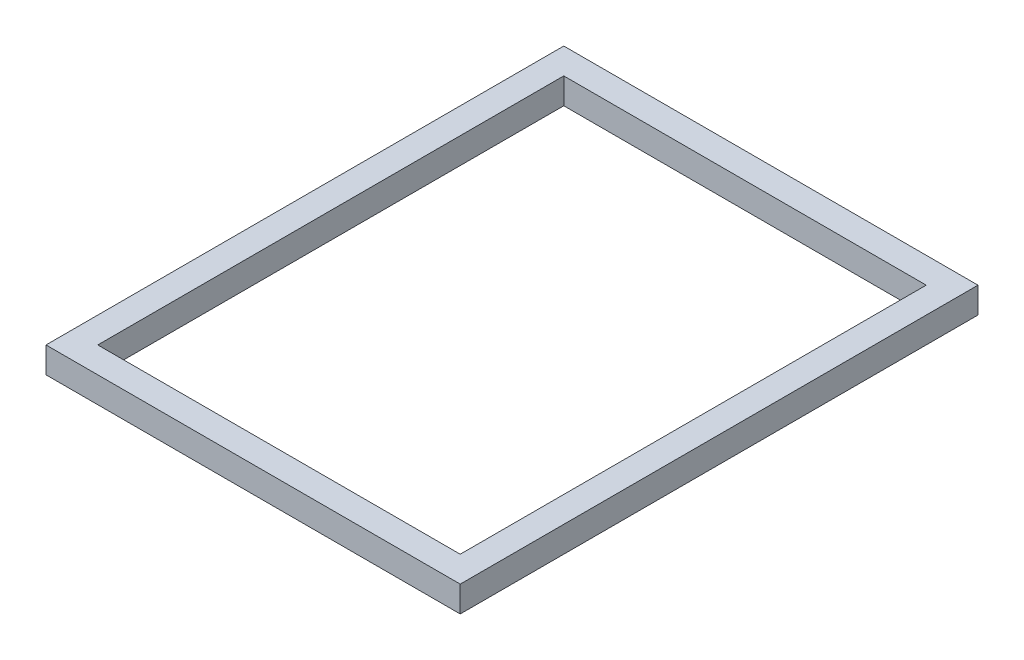
SolidWorks part; units mm, degrees
material "Silicon Rubber"
ref_plane "Front Plane" through (0, 0, 0) normal (0, 0, 1) x (1, 0, 0)
ref_plane "Top Plane" through (0, 0, 0) normal (0, 1, 0) x (1, 0, 0)
ref_plane "Right Plane" through (0, 0, 0) normal (1, 0, 0) x (0, 0, -1)
sketch "Sketch1" plane through (0, 0, 0) normal (0, 1, 0) x (1, 0, 0)
  line L0 (1.5875, 1.5875) -> (1.5875, 30.1625)
  line L1 (0, 0) -> (25.4, 0)
  line L2 (0, 0) -> (0, 31.75)
  line L3 (0, 31.75) -> (25.4, 31.75)
  line L4 (25.4, 0) -> (25.4, 31.75)
  line L5 (1.5875, 30.1625) -> (23.8125, 30.1625)
  line L6 (23.8125, 1.5875) -> (23.8125, 30.1625)
  line L7 (1.5875, 1.5875) -> (23.8125, 1.5875)
  dimension "D2" = 31.75
  dimension "D3" = 25.4
  dimension "D1" = 1.5875
extrude "Boss-Extrude1" add sketch "Sketch1" along normal blind 1.5875
